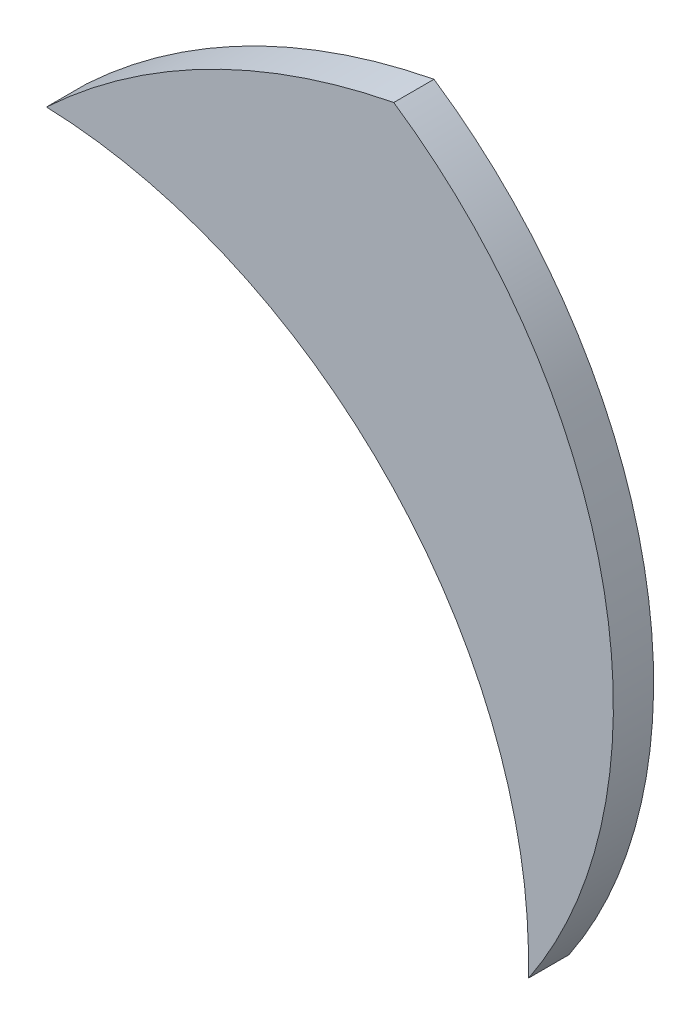
SolidWorks part; units mm, degrees
ref_plane "Front Plane" through (0, 0, 0) normal (0, 0, 1) x (1, 0, 0)
ref_plane "Top Plane" through (0, 0, 0) normal (0, 1, 0) x (1, 0, 0)
ref_plane "Right Plane" through (0, 0, 0) normal (1, 0, 0) x (0, 0, -1)
sketch "Sketch1" plane through (0, 0, 0) normal (0, 0, 1) x (1, 0, 0)
  line L0 (0.0351, 1.1199) -> (0.6348, 0.9431)
  arc A0 (-169.691, 872.6546) -> (-608.0237, 648.5586) centre (0, 0) ccw
  arc A1 (-608.0237, 648.5586) -> (0.0351, 1.1199) centre (-628.2911, 20.2675) cw
  arc A2 (0.6348, 0.9431) -> (-169.691, 872.6546) centre (-521.1728, 351.4818) ccw
  dimension "D1" = 1778
extrude "Boss-Extrude1" add sketch "Sketch1" along normal blind 50.8
sketch "Sketch3" plane through (0, 0, 0) normal (0, 1, 0) x (1, 0, 0)
  line L0 (0, 169.3307) -> (0, -358.4885) construction
pattern_circular "CirPattern2" count 11 over 360 about axis through (0, 0, -169.3307) along (0, 0, 1) of "Boss-Extrude1"
